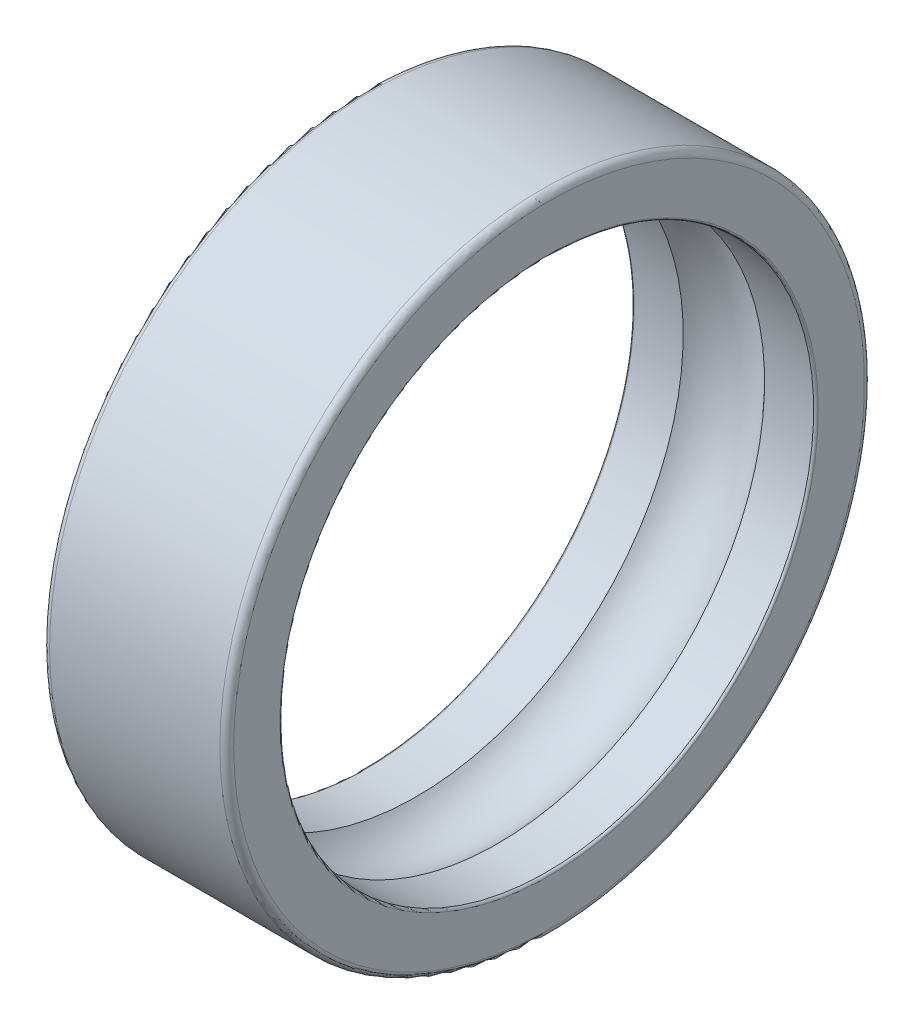
SolidWorks part; units mm, degrees
ref_plane "Plan de face" through (0, 0, 0) normal (0, 0, 1) x (1, 0, 0)
ref_plane "Plan de dessus" through (0, 0, 0) normal (0, 1, 0) x (1, 0, 0)
ref_plane "Plan de droite" through (0, 0, 0) normal (1, 0, 0) x (0, 0, -1)
ref_plane "Plan1" through (0, 0, 0) normal (0, 0, 1) x (1, 0, 0)
sketch "Esquisse1" plane through (0, 0, 0) normal (0, 0, 1) x (1, 0, 0)
  line L0 (0, 13.7) -> (0, 11.695)
  line L1 (0.1, 11.595) -> (2.2322, 11.595)
  line L2 (5.7678, 11.595) -> (7.9, 11.595)
  line L3 (8, 11.695) -> (8, 13.7)
  line L4 (7.7, 14) -> (0.3, 14)
  line L5 (50, 0) -> (-50, 0) construction
  arc A0 (0, 11.695) -> (0.1, 11.595) centre (0.1, 11.695) ccw
  arc A1 (2.2322, 11.595) -> (5.7678, 11.595) centre (4, 10) cw
  arc A2 (7.9, 11.595) -> (8, 11.695) centre (7.9, 11.695) ccw
  arc A3 (8, 13.7) -> (7.7, 14) centre (7.7, 13.7) ccw
  arc A4 (0.3, 14) -> (0, 13.7) centre (0.3, 13.7) ccw
revolve "Révolution1" add sketch "Esquisse1" angle 360 about L5
